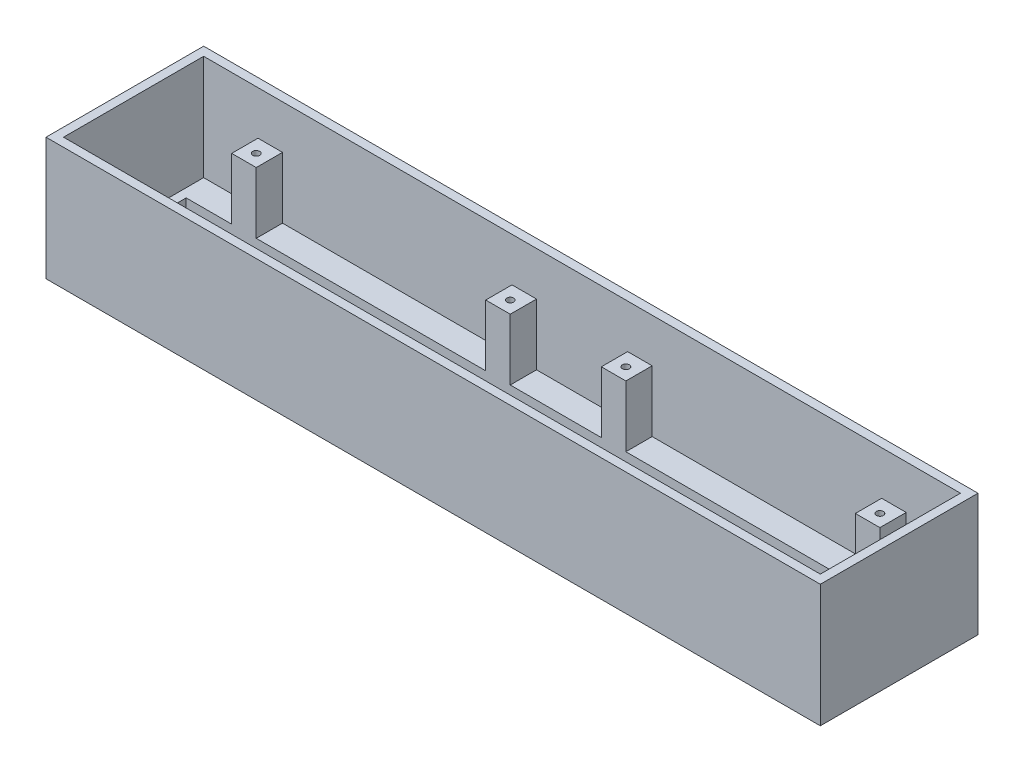
SolidWorks part; units mm, degrees
ref_plane "Front Plane" through (0, 0, 0) normal (0, 0, 1) x (1, 0, 0)
ref_plane "Top Plane" through (0, 0, 0) normal (0, 1, 0) x (1, 0, 0)
ref_plane "Right Plane" through (0, 0, 0) normal (1, 0, 0) x (0, 0, -1)
sketch "Sketch1" plane through (0, 0, 0) normal (0, 1, 0) x (1, 0, 0)
  line L0 (0, 0) -> (0, 46.1847) construction
  line L1 (-110.5, 22.5) -> (110.5, 22.5)
  line L2 (-110.5, 22.5) -> (-110.5, -22.5)
  line L3 (-110.5, -22.5) -> (110.5, -22.5)
  line L4 (110.5, 22.5) -> (110.5, -22.5)
  line L5 (0, 46.1847) -> (0, 0) construction
  line L6 (0, 0) -> (-132.7699, 0) construction
  line L8 (-27.2143, -70.7906) -> (-28.1151, -66.2212) construction
  dimension "D1" = 45
  dimension "D2" = 221
  dimension "D3" = 110.5
  dimension "D4" = 22.5
extrude "Boss-Extrude1" add sketch "Sketch1" along normal blind 5
sketch "Sketch2" plane through (0, 5, 0) normal (0, 1, 0) x (1, 0, 0)
  line L0 (0, 0) -> (0, 63.4853) construction
  line L1 (-105.5, 12.5) -> (105.5, 12.5)
  line L2 (-105.5, 12.5) -> (-105.5, -12.5)
  line L3 (-105.5, -12.5) -> (105.5, -12.5)
  line L4 (105.5, 12.5) -> (105.5, -12.5)
  line L5 (0, 63.4853) -> (0, -74.9421) construction
  line L6 (0, -74.9421) -> (0, 0) construction
  line L7 (0, 0) -> (-181.4639, 0) construction
  line L8 (-181.4639, 0) -> (180.3828, 0) construction
  point P8 (0, -5.7284)
  dimension "D1" = 25
  dimension "D2" = 211
  dimension "D3" = 105.5
  dimension "D4" = 12.5
extrude "Cut-Extrude1" cut sketch "Sketch2" against normal blind 2.5
sketch "Sketch3" plane through (0, 2.5, 0) normal (0, 1, 0) x (1, 0, 0)
  line L0 (0, -84.5319) -> (0, 82.5317) construction
  line L1 (0, 82.5317) -> (0, 0) construction
  line L2 (0, 0) -> (-169.1228, 0) construction
  line L3 (-169.1228, 0) -> (142.1549, 0) construction
  circle A0 centre (-53, 0) radius 8
  circle A1 centre (53, 0) radius 8
  point P10 (0, 0)
  point P11 (0, 0)
  dimension "D1" = 53
  dimension "D2" = 53
extrude "Cut-Extrude2" cut sketch "Sketch3" against normal blind 2.5
sketch "Sketch4" plane through (0, 5, 0) normal (0, 1, 0) x (1, 0, 0)
  line L0 (0, 66.7486) -> (0, -72.9211) construction
  line L1 (0, -72.9211) -> (0, 0) construction
  line L2 (0, 0) -> (-130.6196, 0) construction
  line L3 (-130.6196, 0) -> (143.6753, 0) construction
  point P7 (0, 0)
  point P8 (0, 0)
  point P10 (0, 0)
  point P11 (-88.3077, 24.8032)
sketch "Sketch6" plane through (0, 5, 0) normal (0, 1, 0) x (1, 0, 0)
  line L1 (-110.5, -22.5) -> (110.5, -22.5)
  line L3 (110.5, 22.5) -> (-110.5, 22.5)
  line L6 (-110.5, -20) -> (110.5, -20)
  line L10 (0, 66.7486) -> (0, -72.9211) construction
  line L11 (-110.5, -20) -> (-110.5, -22.5)
  line L12 (110.5, -20) -> (110.5, -22.5)
  line L13 (-110.5, 22.5) -> (-110.5, 20)
  line L14 (-110.5, 22.5) -> (-110.5, -22.5) construction
  line L15 (-110.5, 20) -> (110.5, 20)
  line L16 (110.5, -22.5) -> (110.5, 22.5) construction
  line L17 (110.5, 20) -> (110.5, 22.5)
  line L19 (108, 20) -> (110.5, 20)
  line L20 (108, 20) -> (108, -20)
  line L25 (108, -20) -> (110.5, -20)
  line L26 (110.5, 20) -> (110.5, -20)
  line L31 (-110.5, 20) -> (-108, 20)
  line L32 (-110.5, 20) -> (-110.5, -20)
  line L33 (-110.5, -20) -> (-108, -20)
  line L34 (-108, 20) -> (-108, -20)
  line M12 (-110.5, 22.5) -> (-110.5, -22.5)
  line M14 (110.5, -22.5) -> (110.5, 22.5)
  line M15 (110.5, 22.5) -> (-110.5, 22.5)
  dimension "D2" = 2.5
  dimension "D3" = 2.5
  dimension "D4" = 2.5
  dimension "D6" = 2.5
  dimension "D7" = 40
  dimension "D8" = 108
  dimension "D9" = 221
  dimension "D10" = 2.5
extrude "Boss-Extrude3" add sketch "Sketch6" along normal blind 30 contours L34 L15 L6 M12 | L15 M12 M14 M15 | L20 L25 L26 L19
sketch "Sketch7" plane through (0, 5, 0) normal (0, 1, 0) x (1, 0, 0)
  line L0 (105.5, 12.5) -> (-105.5, 12.5) construction
  line L1 (-92.5, 20) -> (-85.5, 20)
  line L2 (-92.5, 20) -> (-92.5, 12.5)
  line L3 (-92.5, 12.5) -> (-85.5, 12.5)
  line L4 (-85.5, 20) -> (-85.5, 12.5)
  line L5 (-105.5, 12.5) -> (-105.5, -12.5) construction
  line L6 (-105.5, -12.5) -> (105.5, -12.5) construction
  line L7 (-92.5, -12.5) -> (-85.5, -12.5)
  line L8 (-92.5, -12.5) -> (-92.5, -20)
  line L9 (-92.5, -20) -> (-85.5, -20)
  line L10 (-85.5, -12.5) -> (-85.5, -20)
  line L11 (-108, -20) -> (108, -20) construction
  line L14 (-108, 20) -> (108, 20) construction
  line L15 (-20, 20) -> (-13, 20)
  line L16 (-20, 20) -> (-20, 12.5)
  line L17 (-20, 12.5) -> (-13, 12.5)
  line L18 (-13, 20) -> (-13, 12.5)
  line L19 (105.5, 12.5) -> (-105.5, 12.5) construction
  line L20 (0, 66.7486) -> (0, -72.9211) construction
  line L21 (-105.5, -12.5) -> (105.5, -12.5) construction
  line L22 (-20, -12.5) -> (-13, -12.5)
  line L23 (-20, -12.5) -> (-20, -20)
  line L24 (-20, -20) -> (-13, -20)
  line L25 (-13, -12.5) -> (-13, -20)
  line L26 (-108, -20) -> (108, -20) construction
  line L27 (13, 20) -> (20, 20)
  line L28 (13, 20) -> (13, 12.5)
  line L29 (13, 12.5) -> (20, 12.5)
  line L30 (20, 20) -> (20, 12.5)
  line L31 (13, -12.5) -> (20, -12.5)
  line L32 (13, -12.5) -> (13, -20)
  line L33 (13, -20) -> (20, -20)
  line L34 (20, -12.5) -> (20, -20)
  line L35 (105.5, -12.5) -> (105.5, 12.5) construction
  line L36 (85.5, 20) -> (92.5, 20)
  line L37 (85.5, 20) -> (85.5, 12.5)
  line L38 (85.5, 12.5) -> (92.5, 12.5)
  line L39 (92.5, 20) -> (92.5, 12.5)
  line L40 (105.5, -12.5) -> (105.5, 12.5) construction
  line L41 (85.5, -12.5) -> (92.5, -12.5)
  line L42 (85.5, -12.5) -> (85.5, -20)
  line L43 (85.5, -20) -> (92.5, -20)
  line L44 (92.5, -12.5) -> (92.5, -20)
  dimension "D1" = 7
  dimension "D2" = 13
  dimension "D3" = 7
  dimension "D4" = 7
  dimension "D5" = 13
  dimension "D6" = 7.5
  dimension "D7" = 7
  dimension "D8" = 13
  dimension "D9" = 13
  dimension "D10" = 13
  dimension "D11" = 7
  dimension "D12" = 7
  dimension "D13" = 13
  dimension "D14" = 7
  dimension "D15" = 13
  dimension "D16" = 7
  dimension "D17" = 13
extrude "Boss-Extrude4" add sketch "Sketch7" along normal blind 17.5
sketch "Sketch9" plane through (0, 22.5, 0) normal (0, 1, 0) x (1, 0, 0)
  line L0 (-85.5, 12.5) -> (-85.5, 20) construction
  line L1 (-92.5, 12.5) -> (-85.5, 12.5) construction
  line L2 (-85.5, -20) -> (-85.5, -12.5) construction
  line L6 (-105.5, -12.5) -> (105.5, -12.5) construction
  line L7 (-20, 12.5) -> (-13, 12.5) construction
  line L8 (-20, 20) -> (-20, 12.5) construction
  line L10 (-20, -12.5) -> (-20, -20) construction
  line L11 (105.5, 12.5) -> (-105.5, 12.5) construction
  line L12 (13, 20) -> (13, 12.5) construction
  line L13 (20, -20) -> (20, -12.5) construction
  line L14 (92.5, 12.5) -> (92.5, 20) construction
  line L15 (85.5, 12.5) -> (92.5, 12.5) construction
  line L16 (92.5, -12.5) -> (85.5, -12.5) construction
  line L18 (85.5, -12.5) -> (85.5, -20) construction
  circle A0 centre (-89, 16) radius 1
  circle A1 centre (-89, -16) radius 1
  circle A2 centre (-16.5, 16) radius 1
  circle A3 centre (-16.5, -16) radius 1
  circle A4 centre (16.5, 16) radius 1
  circle A5 centre (16.5, -16) radius 1
  circle A6 centre (89, 16) radius 1
  circle A7 centre (89, -16) radius 1
  point P42 (0, 0)
  dimension "D3" = 3.5
  dimension "D5" = 3.5
  dimension "D7" = 3.5
  dimension "D9" = 3.5
  dimension "D11" = 3.5
  dimension "D13" = 3.5
  dimension "D15" = 3.5
  dimension "D1" = 3.5
  dimension "D2" = 3.5
  dimension "D4" = 3.5
  dimension "D6" = 3.5
  dimension "D8" = 3.5
  dimension "D10" = 3.5
  dimension "D12" = 3.5
  dimension "D14" = 3.5
  dimension "D16" = 3.5
extrude "Cut-Extrude3" cut sketch "Sketch9" against normal blind 6
